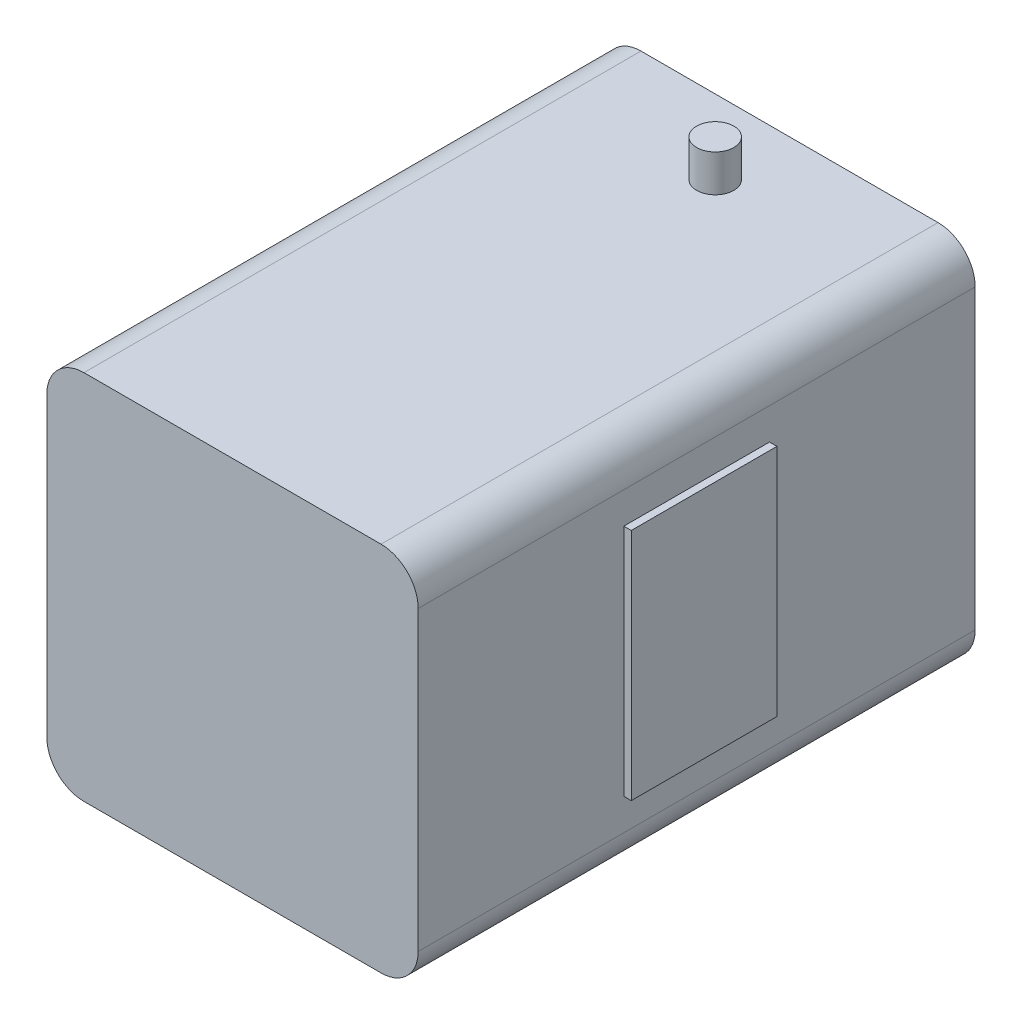
SolidWorks part; units mm, degrees
material "ABS"
ref_plane "Front Plane" through (0, 0, 0) normal (0, 0, 1) x (1, 0, 0)
ref_plane "Top Plane" through (0, 0, 0) normal (0, 1, 0) x (1, 0, 0)
ref_plane "Right Plane" through (0, 0, 0) normal (1, 0, 0) x (0, 0, -1)
sketch "Sketch1" plane through (0, 0, 0) normal (0, 0, 1) x (1, 0, 0)
  line L1 (-50, -50) -> (50, -50)
  line L2 (-50, -50) -> (-50, 50)
  line L3 (-50, 50) -> (50, 50)
  line L4 (50, -50) -> (50, 50)
  line L5 (-50, -50) -> (50, 50) construction
  line L6 (-50, 50) -> (50, -50) construction
  point P0 (0, 0)
  dimension "D1" = 100
  dimension "D2" = 100
extrude "Boss-Extrude1" add sketch "Sketch1" along normal blind 150
fillet "Fillet1" radius 10 4 edges at (-50, 50, 75) (50, 50, 75) (50, -50, 75) (-50, -50, 75)
sketch "Sketch2" plane through (50, 0, 0) normal (1, 0, 0) x (0, 0, -1)
  line L0 (0, 0) -> (-150, 0) construction
  line L1 (-150, -40) -> (-150, 40) construction
  line L3 (-55.3845, -31.5037) -> (-94.6155, -31.5037)
  line L4 (-55.3845, -31.5037) -> (-55.3845, 31.5037)
  line L5 (-55.3845, 31.5037) -> (-94.6155, 31.5037)
  line L6 (-94.6155, -31.5037) -> (-94.6155, 31.5037)
  line L7 (-55.3845, -31.5037) -> (-94.6155, 31.5037) construction
  line L8 (-55.3845, 31.5037) -> (-94.6155, -31.5037) construction
  point P5 (-75, 0)
extrude "Boss-Extrude2" add sketch "Sketch2" along normal blind 2
sketch "Sketch3" plane through (0, -50, 0) normal (0, -1, 0) x (1, 0, 0)
  line L0 (0, 0) -> (0, 20) construction
  circle A0 centre (0, 20) radius 5
  dimension "D2" = 10
  dimension "D1" = 20
extrude "Boss-Extrude3" add sketch "Sketch3" along normal blind 10 and the other way blind 110
